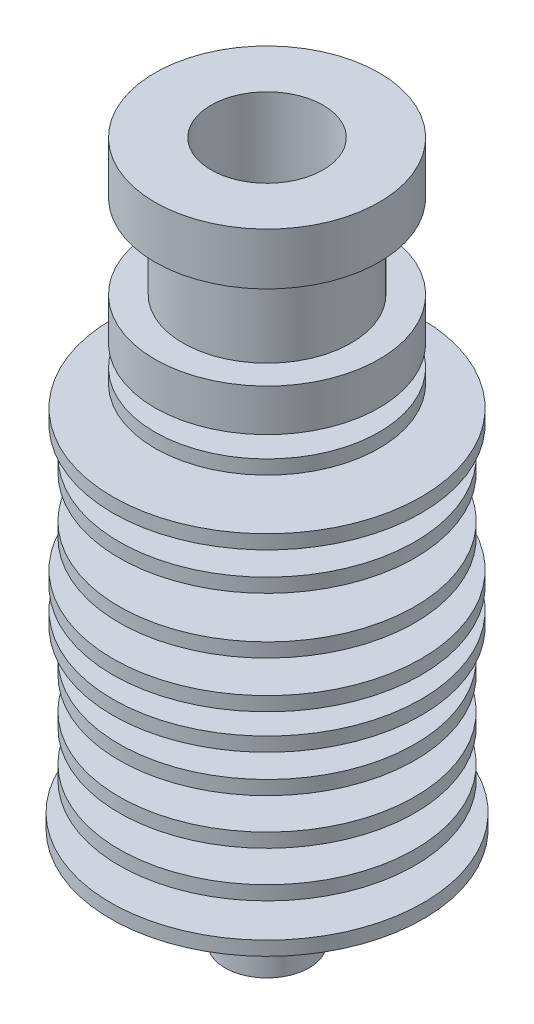
SolidWorks part; units mm, degrees
material "1.5714 (16NiCr4)"
ref_plane "Ebene vorne" through (0, 0, 0) normal (0, 0, 1) x (1, 0, 0)
ref_plane "Ebene oben" through (0, 0, 0) normal (0, 1, 0) x (1, 0, 0)
ref_plane "Ebene rechts" through (0, 0, 0) normal (1, 0, 0) x (0, 0, -1)
sketch "Skizze1" plane through (0, 0, 0) normal (0, 0, 1) x (1, 0, 0)
  line L0 (0, 0) -> (0, 8.4748) construction
  line L1 (4, 0) -> (8, 0)
  line L2 (8, 0) -> (8, -3.7)
  line L3 (8, -3.7) -> (6, -3.7)
  line L4 (6, -3.7) -> (6, -9.7)
  line L5 (6, -9.7) -> (8, -9.7)
  line L6 (8, -9.7) -> (8, -12.7)
  line L7 (8, -12.7) -> (4.5, -12.7)
  line L8 (4.5, -12.7) -> (4.5, -14.2)
  line L9 (4.5, -14.2) -> (8, -14.2)
  line L10 (8, -14.2) -> (8, -15.2)
  line L11 (8, -15.2) -> (4.5, -15.2)
  line L12 (4.5, -15.2) -> (4.5, -16.7)
  line L13 (4.5, -16.7) -> (11, -16.7)
  line L14 (11, -16.7) -> (11, -17.7)
  line L15 (11, -17.7) -> (3.5, -17.7)
  line L16 (3.5, -17.7) -> (3.5, -19.7)
  line L17 (3.5, -19.7) -> (10.55, -19.7)
  line L18 (10.55, -19.7) -> (10.55, -20.7)
  line L19 (10.55, -20.7) -> (3.05, -20.7)
  line L20 (3.05, -20.7) -> (3.05, -23.7)
  line L21 (3.05, -23.7) -> (10.55, -23.7)
  line L22 (10.55, -23.7) -> (10.55, -24.7)
  line L23 (10.55, -24.7) -> (3.5, -24.7)
  line L24 (3.5, -24.7) -> (3.5, -26.7)
  line L25 (3.5, -26.7) -> (11, -26.7)
  line L26 (11, -26.7) -> (11, -27.7)
  line L27 (11, -27.7) -> (7, -27.7)
  line L28 (7, -27.7) -> (7, -29.2)
  line L29 (7, -29.2) -> (11, -29.2)
  line L30 (11, -29.2) -> (11, -30.2)
  line L31 (11, -30.2) -> (3.5, -30.2)
  line L32 (3.5, -30.2) -> (3.5, -32.2)
  line L33 (3.5, -32.2) -> (10.55, -32.2)
  line L34 (10.55, -32.2) -> (10.55, -33.2)
  line L35 (10.55, -33.2) -> (3.05, -33.2)
  line L36 (3.05, -33.2) -> (3.05, -35.45)
  line L37 (3.05, -38.7) -> (10.55, -38.7)
  line L38 (10.55, -38.7) -> (10.55, -39.7)
  line L39 (10.55, -39.7) -> (3.65, -39.7)
  line L40 (3.65, -39.7) -> (3.65, -41.7)
  line L41 (3.65, -41.7) -> (11.15, -41.7)
  line L42 (11.15, -41.7) -> (11.15, -42.7)
  line L43 (11.15, -42.7) -> (2.75, -42.7)
  line L44 (2.75, -42.7) -> (2.75, -44.8)
  line L45 (2.75, -44.8) -> (3, -44.8)
  line L46 (3, -44.8) -> (3, -49.8)
  line L47 (3, -49.8) -> (2, -49.8)
  line L48 (4, 0) -> (4, -6.5)
  line L49 (3.05, -35.45) -> (10.55, -35.45)
  line L50 (10.55, -35.45) -> (10.55, -36.45)
  line L51 (10.55, -36.45) -> (3.05, -36.45)
  line L52 (3.05, -36.45) -> (3.05, -38.7)
  line L53 (4, -6.5) -> (2, -7.9004)
  line L55 (2, -7.9004) -> (2, -49.8)
  dimension "D1" = 16
  dimension "D2" = 12
  dimension "D3" = 16
  dimension "D4" = 22
  dimension "D5" = 1
  dimension "D6" = 1
  dimension "D7" = 22.3
  dimension "D8" = 21.1
  dimension "D9" = 1
  dimension "D10" = 1
  dimension "D11" = 1
  dimension "D12" = 1
  dimension "D13" = 1
  dimension "D14" = 1
  dimension "D15" = 1
  dimension "D16" = 9
  dimension "D17" = 9
  dimension "D18" = 7
  dimension "D19" = 6.1
  dimension "D20" = 7
  dimension "D21" = 14
  dimension "D22" = 7
  dimension "D23" = 6.1
  dimension "D24" = 7.3
  dimension "D25" = 5.5
  dimension "D26" = 6
  dimension "D27" = 2
  dimension "D28" = 2
  dimension "D29" = 5
  dimension "D30" = 7.1
  dimension "D31" = 30
  dimension "D32" = 6
  dimension "D33" = 3.7
  dimension "D34" = 3
  dimension "D35" = 27.5
  dimension "D36" = 25
  dimension "D37" = 2
  dimension "D38" = 12.5
  dimension "D39" = 1
  dimension "D40" = 2
  dimension "D41" = 2.25
  dimension "D42" = 1.5
  dimension "D43" = 8
  dimension "D44" = 4
  dimension "D45" = 6.5
  dimension "D46" = 125
revolve "Rotation1" add sketch "Skizze1" angle 360 about L0
